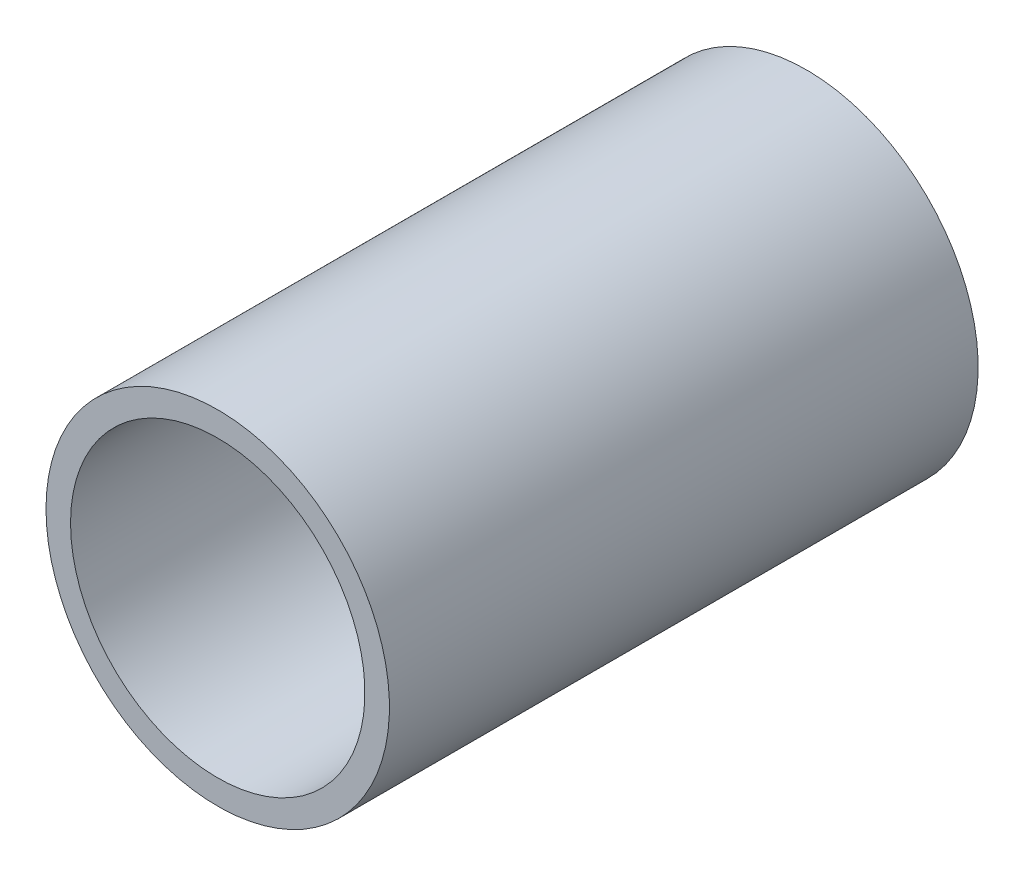
SolidWorks part; units mm, degrees
ref_plane "Front Plane" through (0, 0, 0) normal (0, 0, 1) x (1, 0, 0)
ref_plane "Top Plane" through (0, 0, 0) normal (0, 1, 0) x (1, 0, 0)
ref_plane "Right Plane" through (0, 0, 0) normal (1, 0, 0) x (0, 0, -1)
sketch "Sketch1" plane through (0, 0, 0) normal (0, 0, 1) x (1, 0, 0)
  circle A0 centre (-11.1363, 23.8205) radius 38.1
  circle A1 centre (-11.1363, 23.8205) radius 44.45
  dimension "D1" = 76.2
  dimension "D2" = 88.9
extrude "Boss-Extrude1" add sketch "Sketch1" along normal blind 152.4
